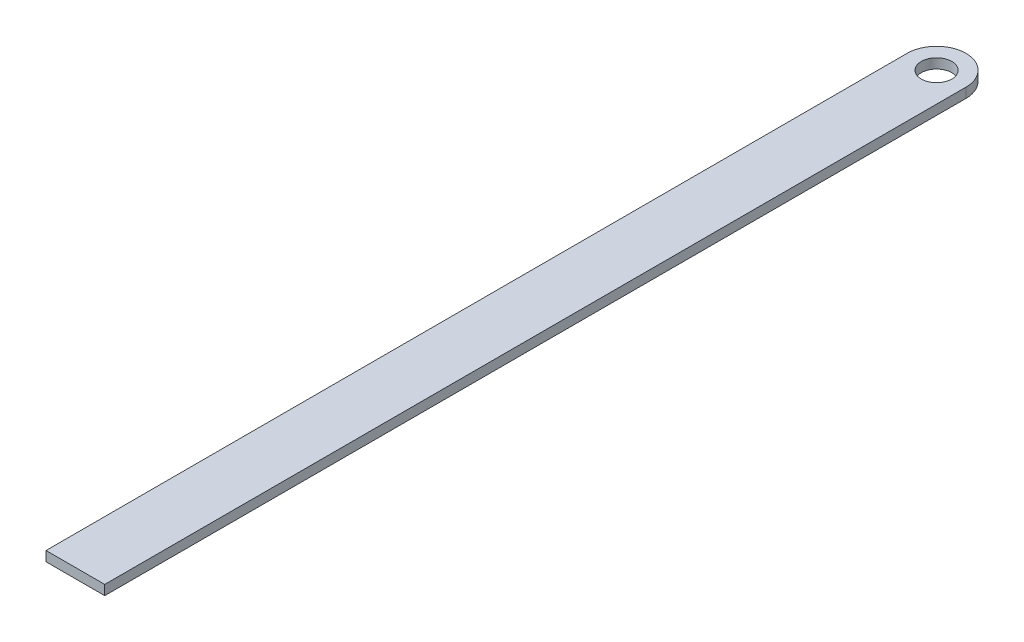
SolidWorks part; units mm, degrees
ref_plane "Front Plane" through (0, 0, 0) normal (0, 0, 1) x (1, 0, 0)
ref_plane "Top Plane" through (0, 0, 0) normal (0, 1, 0) x (1, 0, 0)
ref_plane "Right Plane" through (0, 0, 0) normal (1, 0, 0) x (0, 0, -1)
sketch "Sketch1" plane through (0, 0, 0) normal (0, 1, 0) x (1, 0, 0)
  line L2 (0, 0) -> (0, -139.7)
  line L3 (0, -139.7) -> (9.525, -139.7)
  line L4 (9.525, 0) -> (9.525, -139.7)
  circle A0 centre (4.7625, 0) radius 2.4765
  arc A1 (0, 0) -> (9.525, 0) centre (4.7625, 0) cw
  dimension "D3" = 4.953
  dimension "D1" = 139.7
  dimension "D2" = 9.525
extrude "Boss-Extrude1" add sketch "Sketch1" along normal blind 1.5875
